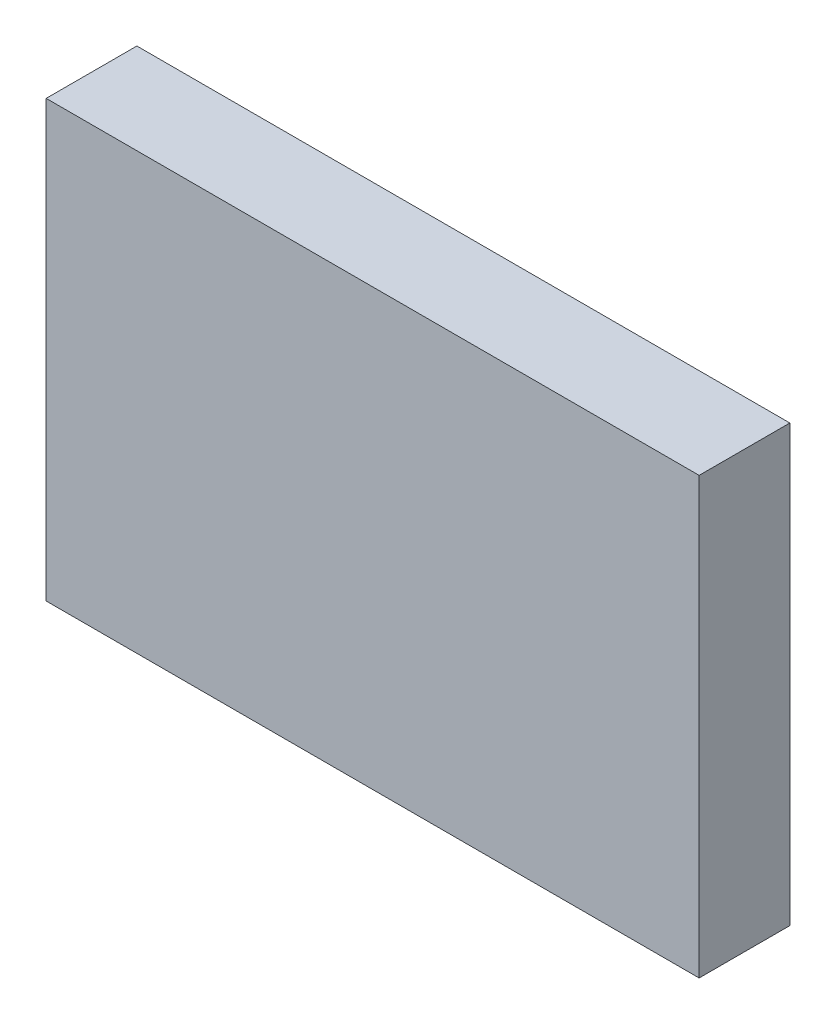
SolidWorks part; units mm, degrees
ref_plane "Ebene vorne" through (0, 0, 0) normal (0, 0, 1) x (1, 0, 0)
ref_plane "Ebene oben" through (0, 0, 0) normal (0, 1, 0) x (1, 0, 0)
ref_plane "Ebene rechts" through (0, 0, 0) normal (1, 0, 0) x (0, 0, -1)
sketch "Skizze1" plane through (0, 0, 0) normal (0, 0, 1) x (1, 0, 0)
  line L1 (-90, -60) -> (90, -60)
  line L2 (-90, -60) -> (-90, 60)
  line L3 (-90, 60) -> (90, 60)
  line L4 (90, -60) -> (90, 60)
  line L5 (-90, -60) -> (90, 60) construction
  line L6 (-90, 60) -> (90, -60) construction
  point P0 (0, 0)
  dimension "D1" = 180
  dimension "D2" = 120
extrude "Aufsatz-Linear austragen1" add sketch "Skizze1" along normal blind 25
